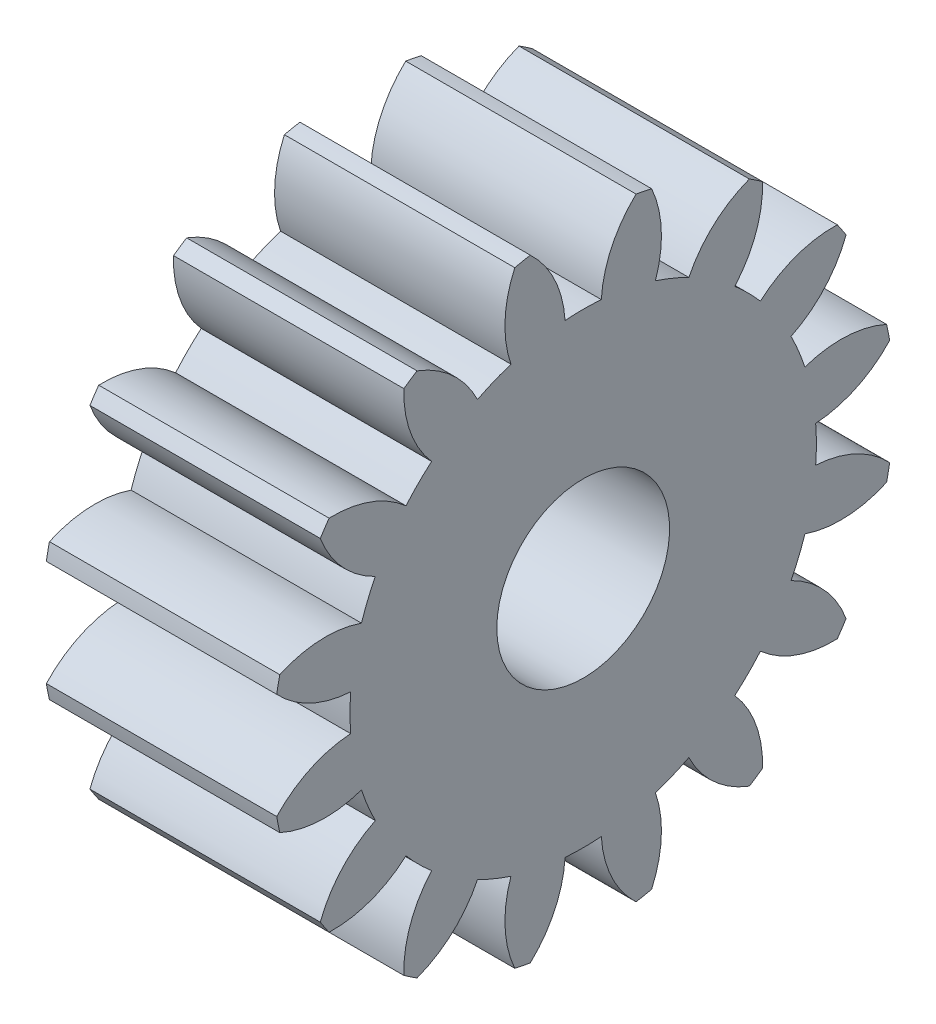
SolidWorks part; units mm, degrees
ref_plane "Plane1" through (0, 0, 0) normal (0, 0, 1) x (1, 0, 0)
ref_plane "Plane2" through (0, 0, 0) normal (0, 1, 0) x (1, 0, 0)
ref_plane "Plane3" through (0, 0, 0) normal (1, 0, 0) x (0, 0, -1)
sketch "HoldingSke" plane through (0, 0, 0) normal (0, 1, 0) x (1, 0, 0)
  line L0 (0, 0) -> (1.6021, -0.4594)
  line L1 (-15, 0) -> (100, 0) construction
  line L2 (0, 0) -> (-2.1039, 2.3779)
  line L3 (0, 0) -> (-11.863, 4.5341)
  line L4 (0, 0) -> (8.3015, 2.3804)
  line L5 (0, 0) -> (-46.8476, -17.4728)
  line L6 (0, 0) -> (-3.3159, -2.2372)
  line L7 (-2.1039, 2.3779) -> (8.6586, 51.2059)
  line L8 (-76.2, 54.61) -> (-75.7, 54.61)
  line L9 (-71.009, 38.7566) -> (-53.1078, 45.2721)
  line L10 (-76.2, 71.12) -> (104.1128, 71.12)
  line L11 (0, 0) -> (-4, 0)
  line L12 (-76.2, 101.6) -> (-76.177, 101.6)
  line L13 (24.9733, 27.94) -> (52.9518, 28.4284)
  line L14 (24.9733, 27.94) -> (24.9743, 27.94)
  line L15 (24.9733, 27.94) -> (100.4006, 29.5858)
  line L16 (-63.627, -0.6) -> (-12.827, -0.6)
  circle A0 centre (0, 0) radius 1.5
  circle A1 centre (0, 0) radius 4.049
  circle A2 centre (0, 0) radius 37.5
  circle A3 centre (0, 0) radius 1.5
  dimension "MHD" = 8.098
  dimension "Hub_dia" = 75
  dimension "Bore" = 3
  dimension "MBD" = 3
  dimension "Num_teeth" = 16
  dimension "Pitch" = 1.6667
  dimension "Overall_len" = 50
  dimension "Show_teeth" = 16
  dimension "Thickness" = 4
  dimension "OAL" = 50.0001
  dimension "T_dim" = 0.5
  dimension "Ap" = 20
  dimension "H" = 19.05
  dimension "Pitch_radius" = 180.3128
  dimension "Width" = 4
  dimension "Backlash" = 0.023
  dimension "Addendum_fac" = 1
  dimension "Dedendum_fac" = 1.25
  dimension "Clearance_fac" = 0.25
  dimension "Dedendum_add" = 0.001
  dimension "Module" = 0.6
sketch "BasProSke" plane through (0, 0, 0) normal (0, 1, 0) x (1, 0, 0)
  line L0 (-10, 0) -> (60, 0) construction
  line L1 (0, 0) -> (0, 5.4)
  line L2 (0, 0) -> (4, 0)
  line L3 (4, 0) -> (4, 5.4)
  line L4 (4, 5.4) -> (0, 5.4)
  dimension "Thickness" = 4
  dimension "Diameter" = 10.8
revolve "Base-Revolve" add sketch "BasProSke" angle 360 about L0
sketch "TooCutSke" plane through (0, 0, 0) normal (1, 0, 0) x (0, 0, -1)
  line L1 (0, 0) -> (0, 107) construction
  line L2 (0, 0) -> (-0.5107, 4.7728) construction
  line L3 (0, 0) -> (-1.8653, 9.3776) construction
  line L4 (-0.5107, 4.7728) -> (-0.9327, 4.6888) construction
  arc A0 (0.3145, 4.0368) -> (-0.3145, 4.0368) centre (0, 0) ccw
  arc A1 (0.9419, 5.343) -> (-0.9419, 5.343) centre (0, 0) ccw
  circle A2 centre (0, 0) radius 4.8 construction
  circle A3 centre (0, 0) radius 4.5105 construction
  arc A4 (-0.3145, 4.0368) -> (-0.9419, 5.343) centre (-2.231, 3.9201) ccw
  arc A5 (0.9419, 5.343) -> (0.3145, 4.0368) centre (2.231, 3.9201) ccw
  dimension "Root_dia" = 8.098
  dimension "Overcut_dia" = 10.8508
  dimension "Pitch_dia" = 9.6
  dimension "Base_dia" = 9.021
  dimension "Flank_rad" = 1.92
  dimension "Half_ang" = 11.25
  dimension "Half_CT" = 0.4302
extrude "ToothCut" cut sketch "TooCutSke" along normal through all
fillet "Breaks" [suppressed] radius 0.012
fillet "RootFillets" [suppressed] radius 0.151
pattern_circular "TeethCuts" count 16 every 22.5 about axis through (-10, 0, 0) along (1, 0, 0) of "ToothCut", "RootFillets", "Breaks"
sketch "HubNeaOneSke" plane through (0, 0, 0) normal (-1, 0, 0) x (0, 0, 1)
  circle A0 centre (0, 0) radius 4.049
  dimension "Diameter" = 8.098
extrude "HubNearOne" [suppressed] add sketch "HubNeaOneSke" along normal blind 46.0001
sketch "HubNeaBotSke" plane through (0, 0, 0) normal (-1, 0, 0) x (0, 0, 1)
  circle A0 centre (0, 0) radius 4.049
  dimension "Diameter" = 8.098
extrude "HubNearBoth" [suppressed] add sketch "HubNeaBotSke" along normal blind 23
ref_plane "FarPln" through (4, 0, 0) normal (1, 0, 0) x (0, 0, -1)
sketch "HubFarSke" plane through (4, 0, 0) normal (1, 0, 0) x (0, 0, -1)
  circle A0 centre (0, 0) radius 4.049
  dimension "Diameter" = 8.098
extrude "HubFar" [suppressed] add sketch "HubFarSke" along normal blind 23
sketch "BorSke" plane through (0, 0, 0) normal (1, 0, 0) x (0, 0, -1)
  circle A0 centre (0, 0) radius 1.5
  dimension "Diameter" = 3
extrude "Bore" cut sketch "BorSke" along normal mid plane 100.0001
sketch "KeySke" plane through (0, 0, 0) normal (1, 0, 0) x (0, 0, -1)
  line L0 (-0.6, 0) -> (-0.6, 2)
  line L1 (-0.6, 2) -> (0.6, 2)
  line L2 (0.6, 2) -> (0.6, 0)
  line L3 (0, 0) -> (0, 34) construction
  line L4 (-0.6, 0) -> (0.6, 0)
  dimension "Offset" = 2
  dimension "Width" = 1.2
extrude "Keyway" [suppressed] cut sketch "KeySke" along normal mid plane 100.0001
pattern_circular "Keyway2" [suppressed] count 2 every 90 about axis through (-10, 0, 0) along (1, 0, 0)
equation "' \"Module@HoldingSke\" = 6.35"
equation "' \"Num_teeth@HoldingSke\" = 12"
equation "' \"Ap@HoldingSke\" =  20"
equation "' \"Ap@HoldingSke\" = 20"
equation "' \"Width@HoldingSke\" = 0.5 * 25.4"
equation "' \"Hub_dia@HoldingSke\"= 1 * 25.4"
equation "' \"Hub_dia@HoldingSke\" = 1 * 25.4"
equation "' \"Overall_len@HoldingSke\" = 1.0 * 25.4"
equation "' \"Bore@HoldingSke\" = 0.75 * 25.4"
equation "' \"T_dim@HoldingSke\" = 0.1 * 25.4"
equation "' \"Width@KeySke\" = 0.25 * 25.4"
equation "' \"Show_teeth@HoldingSke\" = 13"
equation "' \"Backlash@HoldingSke\" = 0.009 * 25.4"
equation "' \"Addendum_fac@HoldingSke\" = 1.0"
equation "' \"Dedendum_fac@HoldingSke\" = 1.25"
equation "' \"Dedendum_add@HoldingSke\" = 0.00005 * 25.4"
equation "' \"Clearance_fac@HoldingSke\" = 0.25"
equation "\"Pitch@HoldingSke\" = 1 / \"Module@HoldingSke\""
equation "\"Overcut_dia@TooCutSke\" = (\"Num_teeth@HoldingSke\" + 2 * \"Addendum_fac@HoldingSke\") / \"Pitch@HoldingSke\" + 0.002 * 25.4"
equation "\"Pitch_dia@TooCutSke\" = \"Num_teeth@HoldingSke\" / \"Pitch@HoldingSke\""
equation "\"Base_dia@TooCutSke\" = \"Num_teeth@HoldingSke\" / \"Pitch@HoldingSke\" * cos((\"Ap@HoldingSke\"  * 3.14159265 / 180))"
equation "\"Root_dia@TooCutSke\" = (\"Num_teeth@HoldingSke\" + 2) / \"Pitch@HoldingSke\" - 2 * (\"Addendum_fac@HoldingSke\" + \"Dedendum_fac@HoldingSke\") / \"Pitch@HoldingSke\" - \"Dedendum_add@HoldingSke\" * 2"
equation "\"Half_ang@TooCutSke\" = 180 / \"Num_teeth@HoldingSke\""
equation "\"Half_CT@TooCutSke\" = \"Num_teeth@HoldingSke\" / \"Pitch@HoldingSke\" * sin((3.14159265 / 2 / \"Num_teeth@HoldingSke\")) / 2 - 7 * \"Backlash@HoldingSke\" / 4"
equation "\"Flank_rad@TooCutSke\" = \"Num_teeth@HoldingSke\" / \"Pitch@HoldingSke\" / 5"
equation "\"Radius@RootFillets\" = \"Clearance_fac@HoldingSke\" / \"Pitch@HoldingSke\" + \"Dedendum_add@HoldingSke\""
equation "\"Break_rad@Breaks\" = 0.02 / \"Pitch@HoldingSke\""
equation "\"Thickness@HoldingSke\" = \"Width@HoldingSke\""
equation "\"OAL@HoldingSke\" = \"Thickness@HoldingSke\""
equation "\"MHD@HoldingSke\" = (\"Num_teeth@HoldingSke\" + 2) / \"Pitch@HoldingSke\" - 2 * (\"Addendum_fac@HoldingSke\" + \"Dedendum_fac@HoldingSke\")  / \"Pitch@HoldingSke\" - \"Dedendum_add@HoldingSke\" * 2"
equation "\"MBD@HoldingSke\" = (\"Num_teeth@HoldingSke\" + 2) / \"Pitch@HoldingSke\" - 2 * (\"Addendum_fac@HoldingSke\" + \"Dedendum_fac@HoldingSke\")  / \"Pitch@HoldingSke\" - \"Dedendum_add@HoldingSke\" * 2 - 0.002 * 25.4"
equation "\"MHD@HoldingSke\" = ((sgn( \"MHD@HoldingSke\" - \"Hub_dia@HoldingSke\" )-1)*( \"MHD@HoldingSke\" - \"Hub_dia@HoldingSke\" ))/-2+ \"Hub_dia@HoldingSke\""
equation "\"MBD@HoldingSke\" = ((sgn( \"MBD@HoldingSke\" - \"Bore@HoldingSke\" )-1)*( \"MBD@HoldingSke\" - \"Bore@HoldingSke\" ))/-2+ \"Bore@HoldingSke\""
equation "\"OAL@HoldingSke\" = ((sgn( \"OAL@HoldingSke\" - \"Overall_len@HoldingSke\" )+1)*( \"OAL@HoldingSke\" - \"Overall_len@HoldingSke\" ))/2 + \"Overall_len@HoldingSke\" + 0.000002 * 25.4"
equation "\"Num_teeth@TeethCuts\" = int( \"Show_teeth@HoldingSke\" ) + 1"
equation "\"Num_teeth@TeethCuts\" = ((sgn( \"Num_teeth@TeethCuts\" - \"Num_teeth@HoldingSke\" )-1)*( \"Num_teeth@TeethCuts\" - \"Num_teeth@HoldingSke\" ))/-2+ \"Num_teeth@HoldingSke\""
equation "\"Num_teeth@TeethCuts\" = ((sgn( \"Num_teeth@TeethCuts\" - 2.0)+1)*( \"Num_teeth@TeethCuts\" - 2.0))/2 +2.0"
equation "\"Angle@TeethCuts\" = 360.0 / \"Num_teeth@HoldingSke\""
equation "\"Diameter@BasProSke\" = (\"Num_teeth@HoldingSke\" + 2 * \"Addendum_fac@HoldingSke\") / \"Pitch@HoldingSke\""
equation "\"Thickness@BasProSke\"  = \"Thickness@HoldingSke\""
equation "' \"Fillet_rad@BasProSke\" =  \"Thickness@HoldingSke\" * 0.05"
equation "' \"Fillet_rad@BasProSke\" = \"Thickness@HoldingSke\" * 0.05"
equation "\"MHD@HoldingSke\" = ((sgn( \"MHD@HoldingSke\" - \"Root_dia@TooCutSke\" )-1)*( \"MHD@HoldingSke\" - \"Root_dia@TooCutSke\" ))/-2+ \"Root_dia@TooCutSke\""
equation "\"Diameter@HubNeaOneSke\" = \"MHD@HoldingSke\""
equation "\"Length@HubNearOne\" = \"OAL@HoldingSke\" - \"Thickness@BasProSke\""
equation "\"Diameter@HubNeaBotSke\" = \"MHD@HoldingSke\""
equation "\"Length@HubNearBoth\" = ( \"OAL@HoldingSke\" - \"Thickness@BasProSke\" ) / 2.0"
equation "\"Thickness@FarPln\" = \"Thickness@BasProSke\""
equation "\"Diameter@HubFarSke\" = \"MHD@HoldingSke\""
equation "\"Length@HubFar\" = ( \"OAL@HoldingSke\" - \"Thickness@BasProSke\" ) / 2.0"
equation "\"Diameter@BorSke\" = \"MBD@HoldingSke\""
equation "\"D1@Bore\" = \"OAL@HoldingSke\" * 2.0"
equation "\"D1@Keyway\" = \"OAL@HoldingSke\" * 2.0"
equation "\"Offset@KeySke\" = \"T_dim@HoldingSke\" + \"MBD@HoldingSke\" / 2.0"
